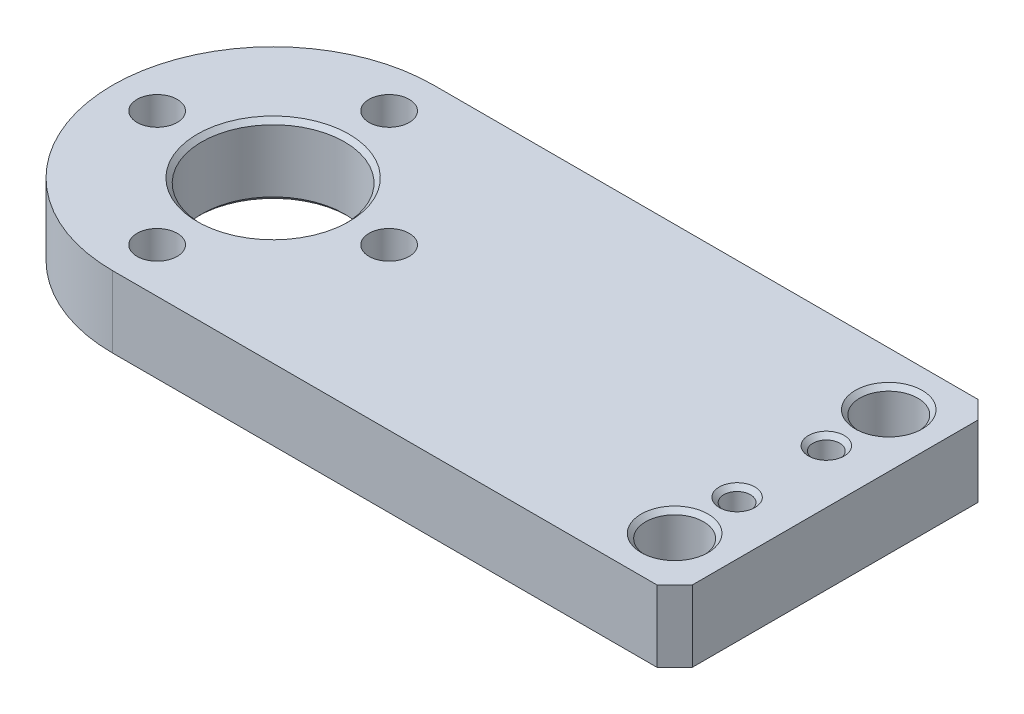
SolidWorks part; units mm, degrees
ref_plane "Front Plane" through (0, 0, 0) normal (0, 0, 1) x (1, 0, 0)
ref_plane "Top Plane" through (0, 0, 0) normal (0, 1, 0) x (1, 0, 0)
ref_plane "Right Plane" through (0, 0, 0) normal (1, 0, 0) x (0, 0, -1)
sketch "Sketch1" plane through (0, 0, 0) normal (0, 1, 0) x (1, 0, 0)
  line L1 (0, 0) -> (63, 0)
  line L3 (0, 36) -> (63, 36)
  line L4 (63, 0) -> (63, 36)
  arc A0 (0, 0) -> (0, 36) centre (0, 18) cw
  dimension "D1" = 63
  dimension "D2" = 36
extrude "Boss-Extrude1" add sketch "Sketch1" along normal blind 8
sketch "Sketch3" plane through (0, 8, 0) normal (0, 1, 0) x (1, 0, 0)
  circle A0 centre (0, 18) radius 8
  dimension "D1" = 16
extrude "Cut-Extrude1" cut sketch "Sketch3" against normal through all
sketch "Sketch4" plane through (0, 8, 0) normal (0, 1, 0) x (1, 0, 0)
  line L0 (63, 36) -> (0, 36) construction
  line L1 (0, 0) -> (63, 0) construction
  circle A0 centre (57, 30) radius 3.25
  circle A1 centre (0, 18) radius 8 construction
  circle A2 centre (57, 6) radius 3.25
  dimension "D1" = 6.5
  dimension "D3" = 6
  dimension "D4" = 6.5
  dimension "D2" = 57
  dimension "D5" = 6
extrude "Cut-Extrude2" cut sketch "Sketch4" against normal through all
sketch "Sketch5" plane through (0, 8, 0) normal (0, 1, 0) x (1, 0, 0)
  line L0 (63, 36) -> (0, 36) construction
  circle A0 centre (57, 23) radius 1.5
  circle A1 centre (57, 30) radius 3.25 construction
  circle A2 centre (57, 13) radius 1.5
  dimension "D3" = 3
  dimension "D4" = 10
  dimension "D5" = 3
  dimension "D1" = 13
  dimension "D2" = 0
extrude "Cut-Extrude3" cut sketch "Sketch5" against normal through all
sketch "Sketch6" plane through (0, 8, 0) normal (0, 1, 0) x (1, 0, 0)
  circle A1 centre (0, 31) radius 2.25
  circle A2 centre (13, 18) radius 2.25
  circle A3 centre (0, 5) radius 2.25
  circle A4 centre (-13, 18) radius 2.25
  dimension "D2" = 4.5
  dimension "D3" = 4.5
  dimension "D4" = 4.5
  dimension "D5" = 4.5
extrude "Cut-Extrude4" cut sketch "Sketch6" against normal through all
chamfer "Chamfer1" distance 0.5 angle 45 10 edges at (57, 0, -26.75) (57, 0, -21.5) (57, 0, -11.5) (57, 0, -2.75) (57, 8, -2.75) (57, 8, -11.5) (57, 8, -21.5) (57, 8, -26.75) (0, 0, -10) (0, 8, -10)
chamfer "Chamfer2" distance 2 angle 45 2 edges at (63, 4, -36) (63, 4, 0)
